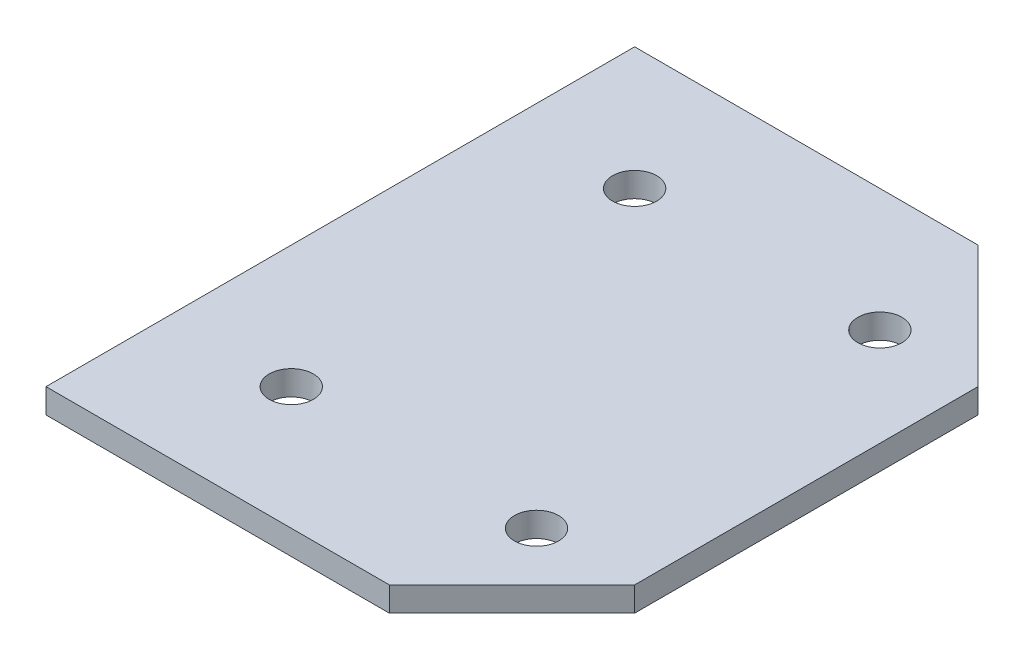
SolidWorks part; units mm, degrees
ref_plane "Front Plane" through (0, 0, 0) normal (0, 0, 1) x (1, 0, 0)
ref_plane "Top Plane" through (0, 0, 0) normal (0, 1, 0) x (1, 0, 0)
ref_plane "Right Plane" through (0, 0, 0) normal (1, 0, 0) x (0, 0, -1)
sketch "Sketch1" plane through (0, 0, 0) normal (0, 1, 0) x (1, 0, 0)
  line L0 (43.2745, -56.635) -> (43.2745, -32.635)
  line L5 (43.2745, -32.635) -> (57.2745, -32.635)
  line L6 (57.2745, -32.635) -> (62.2745, -37.635)
  line L7 (62.2745, -37.635) -> (62.2745, -51.635)
  line L8 (62.2745, -51.635) -> (57.2745, -56.635)
  line L9 (57.2745, -56.635) -> (43.2745, -56.635)
  dimension "D1" = 14
  dimension "D2" = 14
  dimension "D3" = 14
  dimension "D4" = 135
  dimension "D5" = 5
extrude "Boss-Extrude1" add sketch "Sketch1" along normal blind 1
sketch "Sketch2" plane through (0, 1, 0) normal (0, 1, 0) x (1, 0, 0)
  line L0 (62.2745, -51.635) -> (62.2745, -37.635) construction
  line L1 (43.2745, -56.635) -> (57.2745, -56.635) construction
  line L2 (43.2745, -32.635) -> (43.2745, -56.635) construction
  line L3 (57.2745, -32.635) -> (43.2745, -32.635) construction
  circle A0 centre (58.2745, -51.635) radius 0.9
  circle A1 centre (48.2745, -51.635) radius 0.9
  circle A2 centre (48.2745, -37.635) radius 0.9
  circle A3 centre (58.2745, -37.635) radius 0.9
  dimension "D1" = 1.8
  dimension "D2" = 1.8
  dimension "D3" = 1.8
  dimension "D4" = 1.8
  dimension "D5" = 4
  dimension "D6" = 5
  dimension "D7" = 5
  dimension "D8" = 5
  dimension "D9" = 4
  dimension "D10" = 5
  dimension "D11" = 5
  dimension "D12" = 5
extrude "Cut-Extrude1" cut sketch "Sketch2" against normal through all
